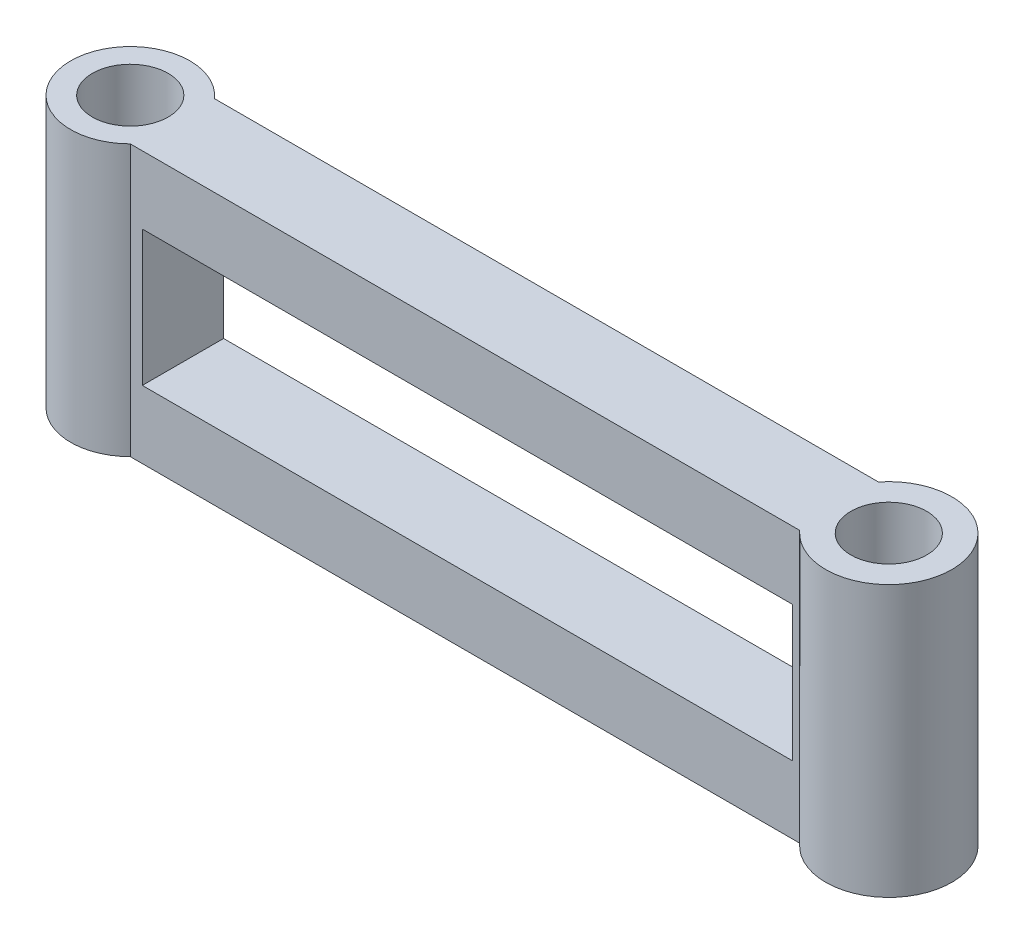
SolidWorks part; units mm, degrees
ref_plane "Front Plane" through (0, 0, 0) normal (0, 0, 1) x (1, 0, 0)
ref_plane "Top Plane" through (0, 0, 0) normal (0, 1, 0) x (1, 0, 0)
ref_plane "Right Plane" through (0, 0, 0) normal (1, 0, 0) x (0, 0, -1)
sketch "Sketch1" plane through (0, 0, 0) normal (0, 1, 0) x (1, 0, 0)
  line L0 (-76.2, -7.7839) -> (-65.6624, 1.3878) construction
  line L5 (-76.2, -7.7839) -> (-66.3217, -17.6622) construction
  line L6 (101.6, -7.7839) -> (89.9995, 1.3878) construction
  line L7 (101.6, -7.7839) -> (90.5949, -17.6622) construction
  line L8 (-65.6624, 1.3878) -> (89.9995, 1.3878)
  line L9 (-66.3217, -17.6622) -> (90.5949, -17.6622)
  circle A1 centre (101.6, -7.7839) radius 8.89
  circle A2 centre (-76.2, -7.7839) radius 8.89
  arc A3 (-65.6624, 1.3878) -> (-66.3217, -17.6622) centre (-76.2, -7.7839) ccw
  arc A4 (90.5949, -17.6622) -> (89.9995, 1.3878) centre (101.6, -7.7839) ccw
  dimension "D1" = 177.8
  dimension "D3" = 19.05
  dimension "D2" = 101.6
  dimension "D4" = 19.05
extrude "Boss-Extrude1" add sketch "Sketch1" along normal blind 63.5
sketch "Sketch2" plane through (0, 0, 17.6622) normal (0, 0, 1) x (1, 0, 0)
  line L1 (-63.5, 47.625) -> (88.9, 47.625)
  line L2 (-63.5, 47.625) -> (-63.5, 15.875)
  line L3 (-63.5, 15.875) -> (88.9, 15.875)
  line L4 (88.9, 47.625) -> (88.9, 15.875)
  dimension "D1" = 31.75
  dimension "D2" = 152.4
  dimension "D3" = 63.5
  dimension "D4" = 15.875
extrude "Cut-Extrude1" cut sketch "Sketch2" against normal through all
